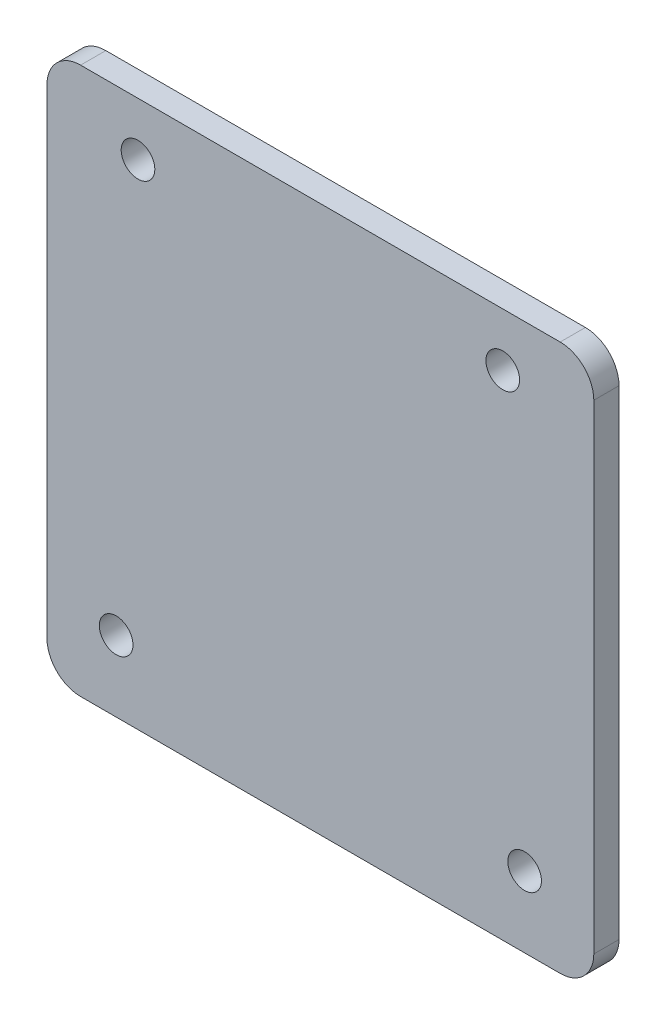
SolidWorks part; units mm, degrees
ref_plane "Front Plane" through (0, 0, 0) normal (0, 0, 1) x (1, 0, 0)
ref_plane "Top Plane" through (0, 0, 0) normal (0, 1, 0) x (1, 0, 0)
ref_plane "Right Plane" through (0, 0, 0) normal (1, 0, 0) x (0, 0, -1)
sketch "Sketch1" plane through (0, 0, 0) normal (0, 0, 1) x (1, 0, 0)
  line L1 (15.2002, 95.2905) -> (72.2596, 95.2905)
  line L2 (11.2002, 91.2905) -> (11.2002, 34.2311)
  line L3 (15.2002, 30.2311) -> (72.2596, 30.2311)
  line L4 (76.2596, 91.2905) -> (76.2596, 34.2311)
  line L5 (43.7299, 62.7608) -> (11.2002, 62.7608) construction
  line L6 (43.7299, 62.7608) -> (43.7299, 97.4608) construction
  line L7 (43.7299, 62.7608) -> (76.2596, 62.7608) construction
  circle A4 centre (19.4299, 38.6608) radius 2
  circle A5 centre (68.0299, 38.6608) radius 2
  circle A6 centre (65.4299, 88.9608) radius 2
  circle A7 centre (22.0299, 88.9608) radius 2
  arc A8 (11.2002, 34.2311) -> (15.2002, 30.2311) centre (15.2002, 34.2311) ccw
  arc A9 (72.2596, 30.2311) -> (76.2596, 34.2311) centre (72.2596, 34.2311) ccw
  arc A10 (72.2596, 95.2905) -> (76.2596, 91.2905) centre (72.2596, 91.2905) cw
  arc A11 (15.2002, 95.2905) -> (11.2002, 91.2905) centre (15.2002, 91.2905) ccw
  point P26 (10.8746, 97.4608)
  point P31 (11.5776, 62.7608)
  point P32 (11.2002, 62.7608)
  dimension "D1" = 4
extrude "Boss-Extrude1" add sketch "Sketch1" along normal blind 3
